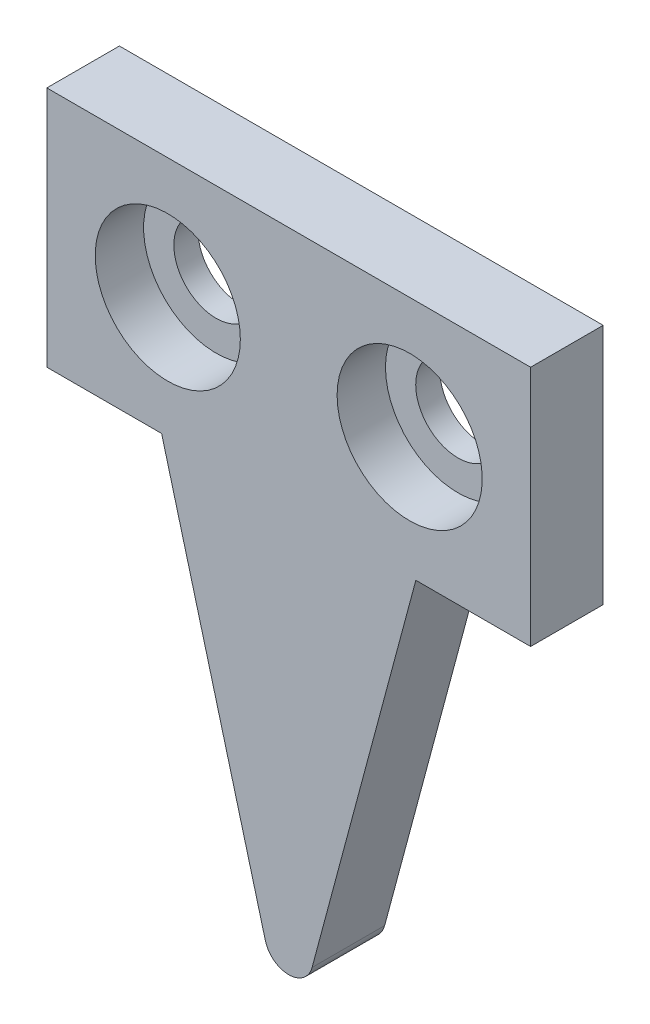
SolidWorks part; units mm, degrees
ref_plane "Front Plane" through (0, 0, 0) normal (0, 0, 1) x (1, 0, 0)
ref_plane "Top Plane" through (0, 0, 0) normal (0, 1, 0) x (1, 0, 0)
ref_plane "Right Plane" through (0, 0, 0) normal (1, 0, 0) x (0, 0, -1)
sketch "Sketch2" plane through (0, 0, 0) normal (0, 0, 1) x (1, 0, 0)
  line L1 (-5.2555, 15.75) -> (-0.9659, -0.2588)
  line L3 (0, -11.1651) -> (0, 29.6028) construction
  line L6 (-5.2555, 15.75) -> (-10, 15.75)
  line L7 (-10, 15.75) -> (-10, 25.75)
  line L8 (-10, 25.75) -> (10, 25.75)
  line L9 (10, 15.75) -> (10, 25.75)
  line L10 (5.2555, 15.75) -> (10, 15.75)
  line L11 (5.2555, 15.75) -> (0.9659, -0.2588)
  arc A0 (-0.9659, -0.2588) -> (0.9659, -0.2588) centre (0, 0) ccw
  point P5 (0, 25.75)
  point P11 (0, 25.75)
  point P13 (0, -1)
  dimension "D4" = 1
  dimension "D1" = 10
  dimension "D2" = 16.75
  dimension "D3" = 20
  dimension "D5" = 105
extrude "Boss-Extrude1" add sketch "Sketch2" along normal blind 3
sketch "Sketch3" plane through (0, 0, 3) normal (0, 0, 1) x (1, 0, 0)
  line L3 (-10, 25.75) -> (-10, 15.75) construction
  line L4 (0, -1) -> (0, 25.75) construction
  line L5 (10, 25.75) -> (-10, 25.75) construction
  circle A0 centre (-5, 20.75) radius 1.75
  arc A1 (-0.9659, -0.2588) -> (0.9659, -0.2588) centre (0, 0) ccw construction
  circle A2 centre (5, 20.75) radius 1.75
  point P9 (-10, 20.75)
  dimension "D1" = 3.5
  dimension "D2" = 5
  dimension "D3" = 5
extrude "Cut-Extrude1" cut sketch "Sketch3" against normal up to surface (3 mm away) up to face at (0, 14.1551, 0)
sketch "Sketch5" plane through (0, 0, 3) normal (0, 0, 1) x (1, 0, 0)
  line L0 (0, -1) -> (0, 25.75) construction
  line L1 (10, 25.75) -> (-10, 25.75) construction
  line L2 (-10, 25.75) -> (-10, 15.75) construction
  arc A0 (-0.9659, -0.2588) -> (0.9659, -0.2588) centre (0, 0) ccw construction
  circle A1 centre (-5, 20.75) radius 3
  circle A2 centre (5, 20.75) radius 3
  point P12 (-10, 20.75)
  dimension "D1" = 6
  dimension "D2" = 5
extrude "Cut-Extrude2" cut sketch "Sketch5" against normal blind 2
